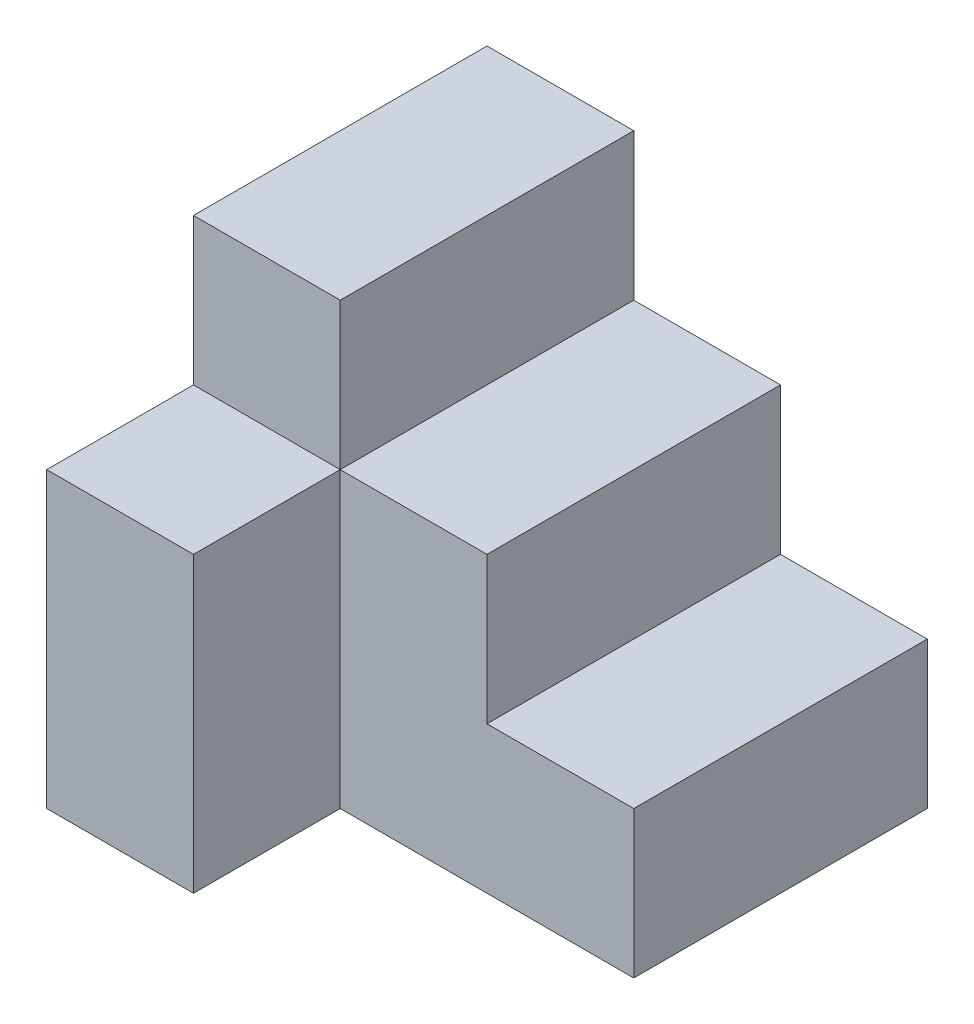
SolidWorks part; units mm, degrees
ref_plane "前基準面" through (0, 0, 0) normal (0, 0, 1) x (1, 0, 0)
ref_plane "上基準面" through (0, 0, 0) normal (0, 1, 0) x (1, 0, 0)
ref_plane "右基準面" through (0, 0, 0) normal (1, 0, 0) x (0, 0, -1)
sketch "草圖1" plane through (0, 0, 0) normal (0, 0, 1) x (1, 0, 0)
  line L1 (0, 0) -> (30, 0)
  line L2 (0, 0) -> (0, 30)
  line L3 (0, 30) -> (30, 30)
  line L4 (30, 0) -> (30, 30)
  dimension "D1" = 30
  dimension "D2" = 30
extrude "填料-伸長1" add sketch "草圖1" against normal blind 30
sketch "草圖2" plane through (0, 0, 0) normal (0, 0, 1) x (1, 0, 0)
  line L0 (10, 30) -> (10, 20)
  line L1 (10, 20) -> (20, 20)
  line L2 (20, 20) -> (20, 10)
  line L3 (20, 10) -> (30, 10)
  line L4 (0, 30) -> (0, 0)
  line L5 (0, 0) -> (30, 0)
  line L6 (30, 0) -> (30, 30)
  line L7 (30, 30) -> (0, 30)
  line L8 (0, 30) -> (0, 0)
  line L9 (0, 0) -> (30, 0)
  line L10 (30, 0) -> (30, 30)
  line L11 (30, 30) -> (0, 30)
  line L12 (30, 0) -> (30, 30) construction
  point P6 (30, 10)
  line M10 (30, 0) -> (30, 30)
  line M11 (30, 30) -> (0, 30)
  dimension "D2" = 20
  dimension "D3" = 10
  dimension "D4" = 20
  dimension "D5" = 10
  dimension "D1" = 0
extrude "除料-伸長1" cut sketch "草圖2" against normal through all contours L2 L3 L0 L1 M10 M11
sketch "草圖3" plane through (0, 30, 0) normal (0, 1, 0) x (1, 0, 0)
  line L1 (10, 0) -> (30, 0)
  line L2 (10, 0) -> (10, 10)
  line L3 (10, 10) -> (30, 10)
  line L4 (30, 0) -> (30, 10)
  dimension "D1" = 20
  dimension "D2" = 10
extrude "除料-伸長2" cut sketch "草圖3" against normal through all
sketch "草圖4" plane through (30, 0, 0) normal (1, 0, 0) x (0, 0, -1)
  line L0 (0, 30) -> (0, 0) construction
  line L1 (30, 30) -> (0, 30) construction
  line L2 (0, 30) -> (0, 0)
  line L3 (30, 30) -> (0, 30)
  line L4 (10, 10) -> (10, 0)
  line L5 (10, 0) -> (30, 0)
  line L6 (30, 0) -> (30, 10)
  line L7 (30, 10) -> (10, 10)
  line L8 (10, 10) -> (10, 0)
  line L9 (10, 0) -> (30, 0)
  line L10 (30, 0) -> (30, 10)
  line L11 (30, 10) -> (10, 10)
  line L12 (10, 30) -> (10, 20)
  line L13 (10, 20) -> (0, 20)
  dimension "D2" = 10
  dimension "D3" = 10
  dimension "D1" = 0
extrude "除料-伸長3" cut sketch "草圖4" against normal through all contours L13 L12 L3 L2
